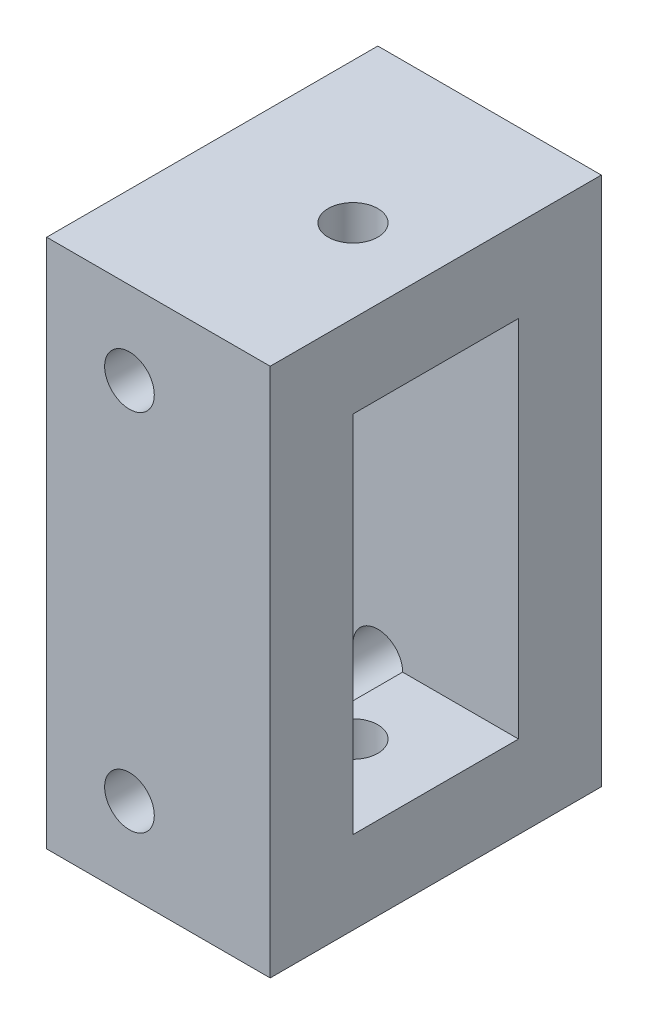
SolidWorks part; units mm, degrees
ref_plane "Front" through (0, 0, 0) normal (0, 0, 1) x (1, 0, 0)
ref_plane "Top" through (0, 0, 0) normal (0, 1, 0) x (1, 0, 0)
ref_plane "Right" through (0, 0, 0) normal (1, 0, 0) x (0, 0, -1)
sketch "Sketch1" plane through (0, 0, 0) normal (0, 1, 0) x (1, 0, 0)
  line L1 (0, 0) -> (13.5, 0)
  line L2 (0, 0) -> (0, -20)
  line L3 (0, -20) -> (13.5, -20)
  line L4 (13.5, 0) -> (13.5, -20)
  dimension "D1" = 13.5
  dimension "D2" = 20
extrude "Boss-Extrude1" add sketch "Sketch1" along normal blind 32
sketch "Sketch2" plane through (0, 0, 20) normal (0, 0, 1) x (1, 0, 0)
  line L0 (0, 32) -> (0, 0) construction
  line L1 (0, 32) -> (13.5, 32) construction
  circle A0 centre (5, 27) radius 1.5
  circle A1 centre (5, 5) radius 1.5
  dimension "D1" = 3
  dimension "D2" = 5
  dimension "D3" = 5
  dimension "D4" = 2
extrude "Cut-Extrude1" cut sketch "Sketch2" against normal through all
sketch "Sketch3" plane through (0, 32, 0) normal (0, 1, 0) x (1, 0, 0)
  line L1 (13.5, -20) -> (13.5, 0) construction
  circle A0 centre (8.5, -10) radius 1.5
  dimension "D1" = 3
  dimension "D2" = 5
extrude "Cut-Extrude2" cut sketch "Sketch3" against normal through all
sketch "Sketch4" plane through (13.5, 0, 0) normal (1, 0, 0) x (0, 0, -1)
  line L0 (-20, 32) -> (0, 32) construction
  line L1 (-15, 27) -> (-5, 27)
  line L2 (-15, 27) -> (-15, 5)
  line L3 (-15, 5) -> (-5, 5)
  line L4 (-5, 27) -> (-5, 5)
  line L5 (-20, 32) -> (-20, 0) construction
  dimension "D1" = 5
  dimension "D2" = 5
  dimension "D3" = 10
  dimension "D4" = 22
extrude "Cut-Extrude3" cut sketch "Sketch4" against normal through all
